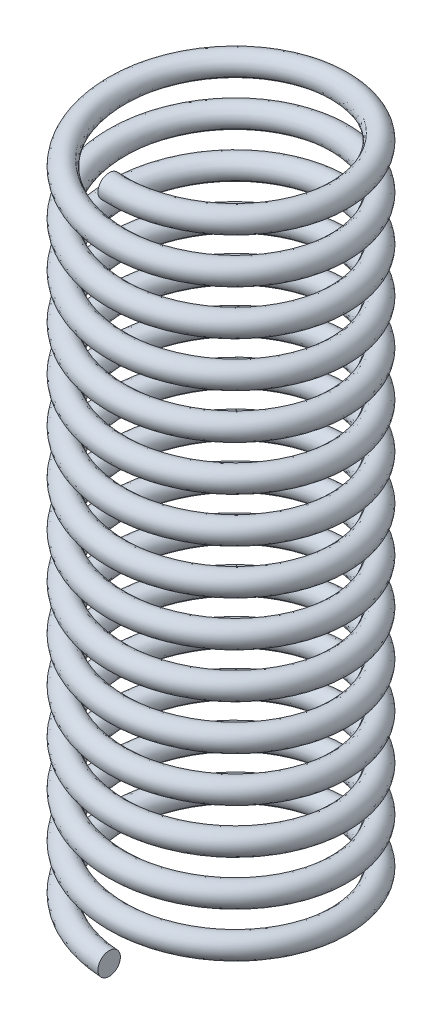
SolidWorks part; units mm, degrees
material "AISI 1020"
ref_plane "Alzado" through (0, 0, 0) normal (0, 0, 1) x (1, 0, 0)
ref_plane "Planta" through (0, 0, 0) normal (0, 1, 0) x (1, 0, 0)
ref_plane "Vista lateral" through (0, 0, 0) normal (1, 0, 0) x (0, 0, -1)
sketch "Croquis1" plane through (0, 0, 0) normal (0, 1, 0) x (1, 0, 0)
  circle A0 centre (0, 0) radius 25
  dimension "D1" = 50
curve "Hélice/Espiral1" pitch 10 height 150 turns 15
sketch "Croquis2" plane through (0, 0, 0) normal (1, 0, 0) x (0, 0, -1)
  circle A0 centre (-24.9007, 149.8586) radius 2.5
  spline S0 degree 3 poles (-25, 0) (-25, 0.1501) (-24.3239, 0.452) (-21.3627, 0.9036) (-16.6915, 1.3554) (-10.6842, 1.8072) (-3.8216, 2.259) (3.3469, 2.7108) (10.2475, 3.1627) (16.3278, 3.6145) (21.1011, 4.0663) (24.1853, 4.5181) (25.3335, 4.9699) (24.4539, 5.4217) (21.6167, 5.8735) (17.0493, 6.3253) (11.117, 6.7771) (4.2949, 7.2289) (-2.871, 7.6807) (-9.8071, 8.1325) (-15.9582, 8.5843) (-20.8318, 9.0361) (-24.0379, 9.488) (-25.3199, 9.9398) (-24.575, 10.3916) (-21.863, 10.8434) (-17.4009, 11.2952) (-11.5459, 11.747) (-4.7667, 12.1988) (2.3941, 12.6506) (9.3632, 13.1024) (15.5829, 13.5542) (20.5551, 14.006) (23.882, 14.4578) (25.2972, 14.9096) (24.6874, 15.3614) (22.1015, 15.8133) (17.7464, 16.2651) (11.9707, 16.7169) (5.2368, 17.1687) (-1.9163, 17.6205) (-8.916, 18.0723) (-15.202, 18.5241) (-20.2711, 18.9759) (-23.7175, 19.4277) (-25.2655, 19.8795) (-24.791, 20.3313) (-22.332, 20.7831) (-18.0854, 21.2349) (-12.3912, 21.6867) (-5.705, 22.1386) (1.4378, 22.5904) (8.4655, 23.0422) (14.8156, 23.494) (19.9798, 23.9458) (23.5446, 24.3976) (25.2247, 24.8494) (24.8856, 25.3012) (22.5545, 25.753) (18.418, 26.2048) (12.8072, 26.6566) (6.1712, 27.1084) (-0.9588, 27.5602) (-8.0121, 28.012) (-14.424, 28.4639) (-19.6813, 28.9157) (-23.3632, 29.3675) (-25.1749, 29.8193) (-24.9714, 30.2711) (-22.769, 30.7229) (-18.744, 31.1747) (-13.2186, 31.6265) (-6.6351, 32.0783) (0.4795, 32.5301) (7.5558, 32.9819) (14.0272, 33.4337) (19.3758, 33.8855) (23.1734, 34.3373) (25.116, 34.7892) (25.0482, 35.241) (22.9753, 35.6928) (19.0633, 36.1446) (13.6254, 36.5964) (7.0967, 37.0482) (0, 37.5) (-7.0967, 37.9518) (-13.6254, 38.4036) (-19.0633, 38.8554) (-22.9753, 39.3072) (-25.0482, 39.759) (-25.116, 40.2108) (-23.1734, 40.6627) (-19.3758, 41.1145) (-14.0272, 41.5663) (-7.5558, 42.0181) (-0.4795, 42.4699) (6.6351, 42.9217) (13.2186, 43.3735) (18.744, 43.8253) (22.769, 44.2771) (24.9714, 44.7289) (25.1749, 45.1807) (23.3632, 45.6325) (19.6813, 46.0843) (14.424, 46.5361) (8.0121, 46.988) (0.9588, 47.4398) (-6.1712, 47.8916) (-12.8072, 48.3434) (-18.418, 48.7952) (-22.5545, 49.247) (-24.8856, 49.6988) (-25.2247, 50.1506) (-23.5446, 50.6024) (-19.9798, 51.0542) (-14.8156, 51.506) (-8.4655, 51.9578) (-1.4378, 52.4096) (5.705, 52.8614) (12.3912, 53.3133) (18.0854, 53.7651) (22.332, 54.2169) (24.791, 54.6687) (25.2655, 55.1205) (23.7175, 55.5723) (20.2711, 56.0241) (15.202, 56.4759) (8.916, 56.9277) (1.9163, 57.3795) (-5.2368, 57.8313) (-11.9707, 58.2831) (-17.7464, 58.7349) (-22.1015, 59.1867) (-24.6874, 59.6386) (-25.2972, 60.0904) (-23.882, 60.5422) (-20.5551, 60.994) (-15.5829, 61.4458) (-9.3632, 61.8976) (-2.3941, 62.3494) (4.7667, 62.8012) (11.5459, 63.253) (17.4009, 63.7048) (21.863, 64.1566) (24.575, 64.6084) (25.3199, 65.0602) (24.0379, 65.512) (20.8318, 65.9639) (15.9582, 66.4157) (9.8071, 66.8675) (2.871, 67.3193) (-4.2949, 67.7711) (-11.117, 68.2229) (-17.0493, 68.6747) (-21.6167, 69.1265) (-24.4539, 69.5783) (-25.3335, 70.0301) (-24.1853, 70.4819) (-21.1011, 70.9337) (-16.3278, 71.3855) (-10.2475, 71.8373) (-3.3469, 72.2892) (3.8216, 72.741) (10.6842, 73.1928) (16.6915, 73.6446) (21.3627, 74.0964) (24.3239, 74.5482) (25.338, 75) (24.3239, 75.4518) (21.3627, 75.9036) (16.6915, 76.3554) (10.6842, 76.8072) (3.8216, 77.259) (-3.3469, 77.7108) (-10.2475, 78.1627) (-16.3278, 78.6145) (-21.1011, 79.0663) (-24.1853, 79.5181) (-25.3335, 79.9699) (-24.4539, 80.4217) (-21.6167, 80.8735) (-17.0493, 81.3253) (-11.117, 81.7771) (-4.2949, 82.2289) (2.871, 82.6807) (9.8071, 83.1325) (15.9582, 83.5843) (20.8318, 84.0361) (24.0379, 84.488) (25.3199, 84.9398) (24.575, 85.3916) (21.863, 85.8434) (17.4009, 86.2952) (11.5459, 86.747) (4.7667, 87.1988) (-2.3941, 87.6506) (-9.3632, 88.1024) (-15.5829, 88.5542) (-20.5551, 89.006) (-23.882, 89.4578) (-25.2972, 89.9096) (-24.6874, 90.3614) (-22.1015, 90.8133) (-17.7464, 91.2651) (-11.9707, 91.7169) (-5.2368, 92.1687) (1.9163, 92.6205) (8.916, 93.0723) (15.202, 93.5241) (20.2711, 93.9759) (23.7175, 94.4277) (25.2655, 94.8795) (24.791, 95.3313) (22.332, 95.7831) (18.0854, 96.2349) (12.3912, 96.6867) (5.705, 97.1386) (-1.4378, 97.5904) (-8.4655, 98.0422) (-14.8156, 98.494) (-19.9798, 98.9458) (-23.5446, 99.3976) (-25.2247, 99.8494) (-24.8856, 100.3012) (-22.5545, 100.753) (-18.418, 101.2048) (-12.8072, 101.6566) (-6.1712, 102.1084) (0.9588, 102.5602) (8.0121, 103.012) (14.424, 103.4639) (19.6813, 103.9157) (23.3632, 104.3675) (25.1749, 104.8193) (24.9714, 105.2711) (22.769, 105.7229) (18.744, 106.1747) (13.2186, 106.6265) (6.6351, 107.0783) (-0.4795, 107.5301) (-7.5558, 107.9819) (-14.0272, 108.4337) (-19.3758, 108.8855) (-23.1734, 109.3373) (-25.116, 109.7892) (-25.0482, 110.241) (-22.9753, 110.6928) (-19.0633, 111.1446) (-13.6254, 111.5964) (-7.0967, 112.0482) (0, 112.5) (7.0967, 112.9518) (13.6254, 113.4036) (19.0633, 113.8554) (22.9753, 114.3072) (25.0482, 114.759) (25.116, 115.2108) (23.1734, 115.6627) (19.3758, 116.1145) (14.0272, 116.5663) (7.5558, 117.0181) (0.4795, 117.4699) (-6.6351, 117.9217) (-13.2186, 118.3735) (-18.744, 118.8253) (-22.769, 119.2771) (-24.9714, 119.7289) (-25.1749, 120.1807) (-23.3632, 120.6325) (-19.6813, 121.0843) (-14.424, 121.5361) (-8.0121, 121.988) (-0.9588, 122.4398) (6.1712, 122.8916) (12.8072, 123.3434) (18.418, 123.7952) (22.5545, 124.247) (24.8856, 124.6988) (25.2247, 125.1506) (23.5446, 125.6024) (19.9798, 126.0542) (14.8156, 126.506) (8.4655, 126.9578) (1.4378, 127.4096) (-5.705, 127.8614) (-12.3912, 128.3133) (-18.0854, 128.7651) (-22.332, 129.2169) (-24.791, 129.6687) (-25.2655, 130.1205) (-23.7175, 130.5723) (-20.2711, 131.0241) (-15.202, 131.4759) (-8.916, 131.9277) (-1.9163, 132.3795) (5.2368, 132.8313) (11.9707, 133.2831) (17.7464, 133.7349) (22.1015, 134.1867) (24.6874, 134.6386) (25.2972, 135.0904) (23.882, 135.5422) (20.5551, 135.994) (15.5829, 136.4458) (9.3632, 136.8976) (2.3941, 137.3494) (-4.7667, 137.8012) (-11.5459, 138.253) (-17.4009, 138.7048) (-21.863, 139.1566) (-24.575, 139.6084) (-25.3199, 140.0602) (-24.0379, 140.512) (-20.8318, 140.9639) (-15.9582, 141.4157) (-9.8071, 141.8675) (-2.871, 142.3193) (4.2949, 142.7711) (11.117, 143.2229) (17.0493, 143.6747) (21.6167, 144.1265) (24.4539, 144.5783) (25.3335, 145.0301) (24.1853, 145.4819) (21.1011, 145.9337) (16.3278, 146.3855) (10.2475, 146.8373) (3.3469, 147.2892) (-3.8216, 147.741) (-10.6842, 148.1928) (-16.6915, 148.6446) (-21.3627, 149.0964) (-24.3239, 149.548) (-25, 149.8499) (-25, 150) knots 0 0 0 0 0.003012 0.006024 0.009036 0.012048 0.01506 0.018072 0.021084 0.024096 0.027108 0.03012 0.033133 0.036145 0.039157 0.042169 0.045181 0.048193 0.051205 0.054217 0.057229 0.060241 0.063253 0.066265 0.069277 0.072289 0.075301 0.078313 0.081325 0.084337 0.087349 0.090361 0.093373 0.096386 0.099398 0.10241 0.105422 0.108434 0.111446 0.114458 0.11747 0.120482 0.123494 0.126506 0.129518 0.13253 0.135542 0.138554 0.141566 0.144578 0.14759 0.150602 0.153614 0.156627 0.159639 0.162651 0.165663 0.168675 0.171687 0.174699 0.177711 0.180723 0.183735 0.186747 0.189759 0.192771 0.195783 0.198795 0.201807 0.204819 0.207831 0.210843 0.213855 0.216867 0.21988 0.222892 0.225904 0.228916 0.231928 0.23494 0.237952 0.240964 0.243976 0.246988 0.25 0.253012 0.256024 0.259036 0.262048 0.26506 0.268072 0.271084 0.274096 0.277108 0.28012 0.283133 0.286145 0.289157 0.292169 0.295181 0.298193 0.301205 0.304217 0.307229 0.310241 0.313253 0.316265 0.319277 0.322289 0.325301 0.328313 0.331325 0.334337 0.337349 0.340361 0.343373 0.346386 0.349398 0.35241 0.355422 0.358434 0.361446 0.364458 0.36747 0.370482 0.373494 0.376506 0.379518 0.38253 0.385542 0.388554 0.391566 0.394578 0.39759 0.400602 0.403614 0.406627 0.409639 0.412651 0.415663 0.418675 0.421687 0.424699 0.427711 0.430723 0.433735 0.436747 0.439759 0.442771 0.445783 0.448795 0.451807 0.454819 0.457831 0.460843 0.463855 0.466867 0.46988 0.472892 0.475904 0.478916 0.481928 0.48494 0.487952 0.490964 0.493976 0.496988 0.5 0.503012 0.506024 0.509036 0.512048 0.51506 0.518072 0.521084 0.524096 0.527108 0.53012 0.533133 0.536145 0.539157 0.542169 0.545181 0.548193 0.551205 0.554217 0.557229 0.560241 0.563253 0.566265 0.569277 0.572289 0.575301 0.578313 0.581325 0.584337 0.587349 0.590361 0.593373 0.596386 0.599398 0.60241 0.605422 0.608434 0.611446 0.614458 0.61747 0.620482 0.623494 0.626506 0.629518 0.63253 0.635542 0.638554 0.641566 0.644578 0.64759 0.650602 0.653614 0.656627 0.659639 0.662651 0.665663 0.668675 0.671687 0.674699 0.677711 0.680723 0.683735 0.686747 0.689759 0.692771 0.695783 0.698795 0.701807 0.704819 0.707831 0.710843 0.713855 0.716867 0.71988 0.722892 0.725904 0.728916 0.731928 0.73494 0.737952 0.740964 0.743976 0.746988 0.75 0.753012 0.756024 0.759036 0.762048 0.76506 0.768072 0.771084 0.774096 0.777108 0.78012 0.783133 0.786145 0.789157 0.792169 0.795181 0.798193 0.801205 0.804217 0.807229 0.810241 0.813253 0.816265 0.819277 0.822289 0.825301 0.828313 0.831325 0.834337 0.837349 0.840361 0.843373 0.846386 0.849398 0.85241 0.855422 0.858434 0.861446 0.864458 0.86747 0.870482 0.873494 0.876506 0.879518 0.88253 0.885542 0.888554 0.891566 0.894578 0.89759 0.900602 0.903614 0.906627 0.909639 0.912651 0.915663 0.918675 0.921687 0.924699 0.927711 0.930723 0.933735 0.936747 0.939759 0.942771 0.945783 0.948795 0.951807 0.954819 0.957831 0.960843 0.963855 0.966867 0.96988 0.972892 0.975904 0.978916 0.981928 0.98494 0.987952 0.990964 0.993976 0.996988 1 1 1 1 construction
  dimension "D1" = 5
sweep "Barrer1" add profiles "Croquis2" path "Hélice/Espiral1"
